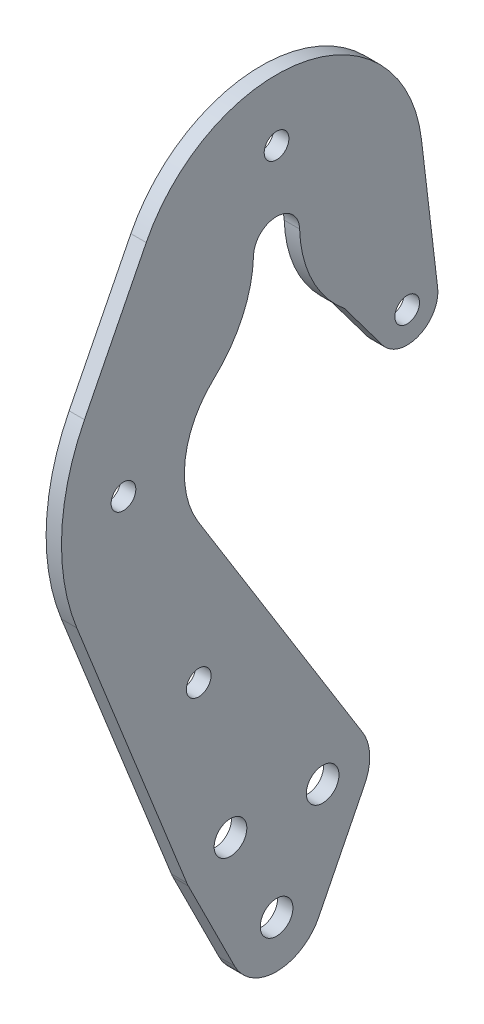
SolidWorks part; units mm, degrees
material "6061-T6 (SS)"
ref_plane "Front" through (0, 0, 0) normal (0, 0, 1) x (1, 0, 0)
ref_plane "Top" through (0, 0, 0) normal (0, 1, 0) x (1, 0, 0)
ref_plane "Right" through (0, 0, 0) normal (1, 0, 0) x (0, 0, -1)
sketch "Sketch1" plane through (0, 0, 0) normal (1, 0, 0) x (0, 0, -1)
  line L0 (-9.525, 0) -> (9.525, 0) construction
  line L1 (18.2262, -4.3506) -> (8.7012, -23.4006)
  line L2 (-18.5611, -3.6036) -> (-41.2879, 53.3845)
  line L3 (-16.1802, 59.795) -> (17.7877, 5.1348)
  line L4 (-8.7012, -23.4006) -> (-18.2262, -4.3506)
  line L5 (0, 0) -> (0, -6.8989) construction
  line L6 (-39.6951, 89.8525) -> (-26.936, 115.1731)
  line L7 (29.9531, 105.1478) -> (33.2934, 76.9469)
  line L8 (21.9075, 72.39) -> (14.0511, 82.8653)
  circle A0 centre (9.525, 0) radius 3.3782
  circle A1 centre (-9.525, 0) radius 3.3782
  circle A4 centre (0, 69.85) radius 19.05 construction
  arc A5 (4.7603, 101.7441) -> (-4.7603, 101.7441) centre (0, 101.6) ccw
  arc A6 (-4.7603, 101.7441) -> (-12.9209, 83.8483) centre (-30.1487, 102.5128) cw
  arc A7 (4.7603, 101.7441) -> (14.0511, 82.8653) centre (30.1487, 102.5128) ccw
  arc A8 (-39.6951, 89.8525) -> (-41.2879, 53.3845) centre (0, 69.85) ccw
  arc A9 (18.2262, -4.3506) -> (17.7877, 5.1348) centre (9.525, 0) ccw
  arc A10 (-18.2262, -4.3506) -> (-18.5611, -3.6036) centre (-9.525, 0) cw
  arc A11 (-26.936, 115.1731) -> (29.9531, 105.1478) centre (0, 101.6) cw
  circle A12 centre (0, -19.05) radius 3.3782
  circle A13 centre (0, -19.05) radius 9.7282 construction
  circle A14 centre (-9.525, 0) radius 9.7282 construction
  circle A15 centre (9.525, 0) radius 9.7282 construction
  arc A16 (8.7012, -23.4006) -> (-8.7012, -23.4006) centre (0, -19.05) cw
  arc A17 (33.2934, 76.9469) -> (21.9075, 72.39) centre (26.9875, 76.2) cw
  arc A18 (-16.1802, 59.795) -> (-12.9209, 83.8483) centre (0, 69.85) cw
  dimension "D1" = 6.7564
  dimension "D2" = 19.05
  dimension "D3" = 38.1
  dimension "D4" = 9.525
  dimension "D5" = 25.4
  dimension "D6" = 31.75
  dimension "D7" = 101.6
  dimension "D8" = 25.4
  dimension "D9" = 6.35
  dimension "D10" = 6.35
  dimension "D11" = 76.2
  dimension "D12" = 25.4
  dimension "D13" = 6.7564
  dimension "D15" = 6.35
  dimension "D14" = 19.05
extrude "Boss-Extrude1" add sketch "Sketch1" along normal blind 3.175 contours L3 A18 A6 A5 A7 L8 A17 L7 A11 L6 A8 L2 A10 L4 A16 L1 A9 A0 A1 A12
hole_wizard "#10 Clearance Hole1" positions "Sketch2" profile "Sketch3" hole size "#10" standard "ANSI Inch" end condition through all
sketch "Sketch2" plane through (3.175, 0, 0) normal (1, 0, 0) x (0, 0, -1)
  line L0 (-44.4077, 71.7895) -> (-18.8775, 72.408) construction
  line L2 (-29.6329, 24.1592) -> (-2.5397, 37.845) construction
  line L3 (-18.5611, -3.6036) -> (-41.2879, 53.3845) construction
  line L4 (-16.1802, 59.795) -> (17.7877, 5.1348) construction
  line L6 (-28.1558, 54.8954) -> (-6.271, 11.5713) construction
  line L8 (0, 106.3625) -> (0, 131.7625) construction
  arc A0 (-39.6951, 89.8525) -> (-41.2879, 53.3845) centre (0, 69.85) ccw construction
  arc A1 (-12.9209, 83.8483) -> (-16.1802, 59.795) centre (0, 69.85) ccw construction
  arc A2 (4.7603, 101.7441) -> (-4.7603, 101.7441) centre (0, 101.6) ccw construction
  arc A3 (29.9531, 105.1478) -> (-26.936, 115.1731) centre (0, 101.6) ccw construction
  point P0 (-16.0863, 31.0021)
  point P2 (-31.6426, 72.0988)
  point P4 (0, 119.0625)
  point P6 (26.9875, 76.2)
  dimension "D1" = 34.925
sketch "Sketch3" plane through (3.175, 31.0021, 16.0863) normal (0, 1, 0) x (0, 0, -1)
  line L0 (0, 0) -> (0, 3.175)
  line L1 (0, 3.175) -> (2.5527, 3.175)
  line L2 (2.5527, 3.175) -> (2.5527, 0)
  line L5 (2.5527, 0) -> (0, 0)
  line L11 (0, -6.35) -> (0, 107.95) construction
  dimension "Thru Hole Dia." = 5.1054
  dimension "Thru Hole Depth" = 3.175
sketch "Sketch4" plane through (0, 0, 0) normal (1, 0, 0) x (0, 0, -1)
  circle A0 centre (0.5537, 97.995) radius 3.5052
  circle A4 centre (0.5537, 89.6638) radius 8.3312 construction
  circle A5 centre (8.8849, 89.6638) radius 3.5052
  circle A6 centre (0.5537, 81.3326) radius 3.5052
  circle A7 centre (-7.7775, 89.6638) radius 3.5052
  point P13 (0.5537, 89.6638)
  dimension "D1" = 7.0104
  dimension "D2" = 4
  dimension "D3" = 9.652
